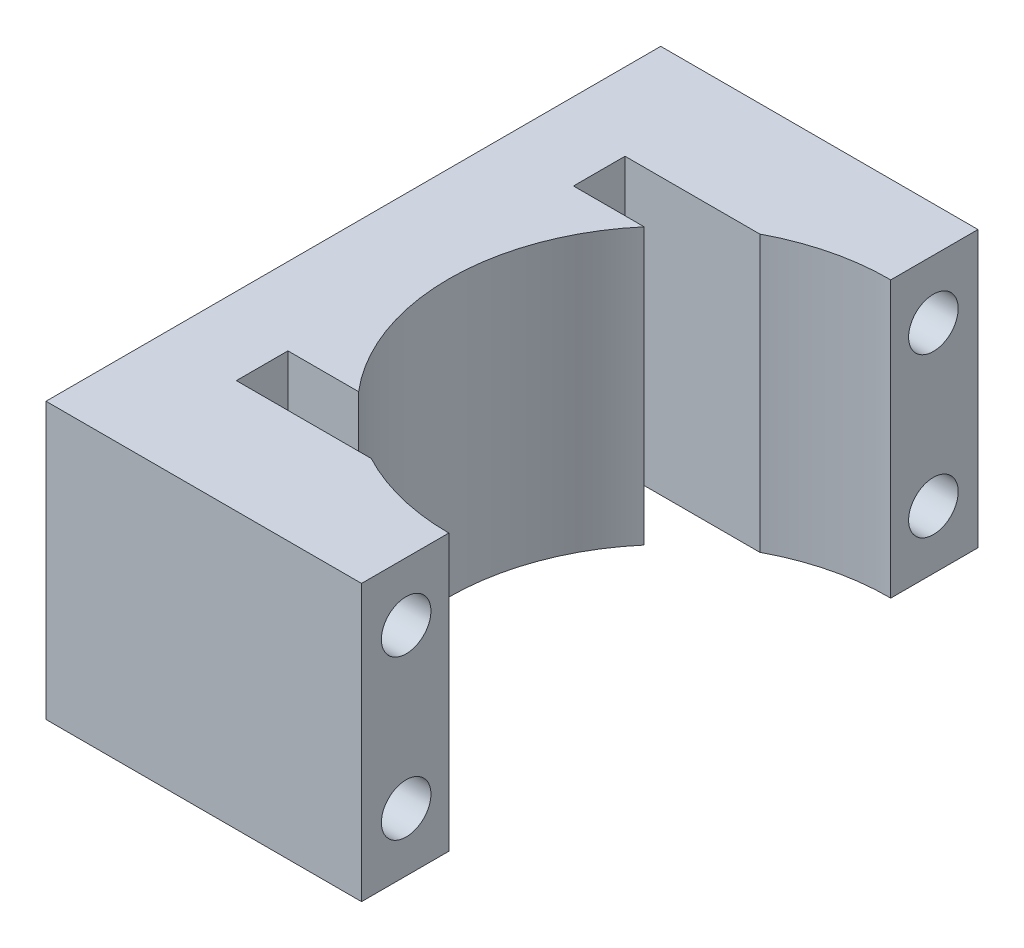
SolidWorks part; units mm, degrees
ref_plane "前视基准面" through (0, 0, 0) normal (0, 0, 1) x (1, 0, 0)
ref_plane "上视基准面" through (0, 0, 0) normal (0, 1, 0) x (1, 0, 0)
ref_plane "右视基准面" through (0, 0, 0) normal (1, 0, 0) x (0, 0, -1)
other "Configuration Table"
sketch "草图1" plane through (0, 0, 0) normal (0, 1, 0) x (1, 0, 0)
  line L0 (0, 15.5) -> (31.825, 15.5) construction
  line L1 (0, 0) -> (15.9125, 0)
  line L2 (0, 0) -> (0, 31)
  line L3 (0, 31) -> (16, 31)
  line L5 (16, 26.5997) -> (16, 31)
  line L6 (15.9125, 4.4) -> (15.9125, 0)
  line L7 (3.9, 5.7) -> (3.9, 8.3)
  line L8 (3.9, 25.3) -> (10.7, 25.3)
  line L9 (3.9, 5.7) -> (10.7, 5.7)
  line L10 (3.9, 22.7) -> (7.4644, 22.7)
  line L11 (3.9, 8.3) -> (7.4644, 8.3)
  line L12 (3.9, 22.7) -> (3.9, 25.3)
  arc A4 (16, 26.5997) -> (10.7, 25.3) centre (15.9125, 15.5) ccw
  arc A5 (7.4644, 22.7) -> (7.4644, 8.3) centre (15.9125, 15.5) ccw
  arc A6 (10.7, 5.7) -> (15.9125, 4.4) centre (15.9125, 15.5) ccw
  point P1 (16, 28.7998)
  dimension "D1" = 19.6
  dimension "D5" = 11.1
  dimension "D6" = 5.3
  dimension "D2" = 16
  dimension "D3" = 31
  dimension "D4" = 12.1
  dimension "D7" = 4.4
  dimension "D8" = 2.6
  dimension "D9" = 2.6
extrude "凸台-拉伸1" add sketch "草图1" along normal blind 13.9
sketch "草图2" plane through (0, 0, 0) normal (-1, 0, 0) x (0, 0, 1)
  line L0 (-28.75, 10.95) -> (-2.25, 10.95) construction
  line L1 (-28.75, 10.95) -> (-28.75, 2.95) construction
  line L2 (-15.5, 13.9) -> (-15.5, 0) construction
  line L3 (-31, 13.9) -> (0, 13.9) construction
  line L4 (-31, 0) -> (0, 0) construction
  line L5 (-31, 6.95) -> (0, 6.95) construction
  line L6 (-31, 13.9) -> (-31, 0) construction
  line L7 (0, 13.9) -> (0, 0) construction
  circle A0 centre (-28.75, 10.95) radius 1.25
  circle A1 centre (-2.25, 10.95) radius 1.25
  circle A2 centre (-2.25, 2.95) radius 1.25
  circle A3 centre (-28.75, 2.95) radius 1.25
  dimension "D1" = 2.5
  dimension "D3" = 26.5
  dimension "D4" = 8
  dimension "D6" = 4
  dimension "D7" = 13.25
  dimension "D8" = 90
  dimension "D2" = 2
  dimension "D5" = 2
extrude "切除-拉伸1" cut sketch "草图2" against normal through all contours A0 | A3 | A1 | A2
